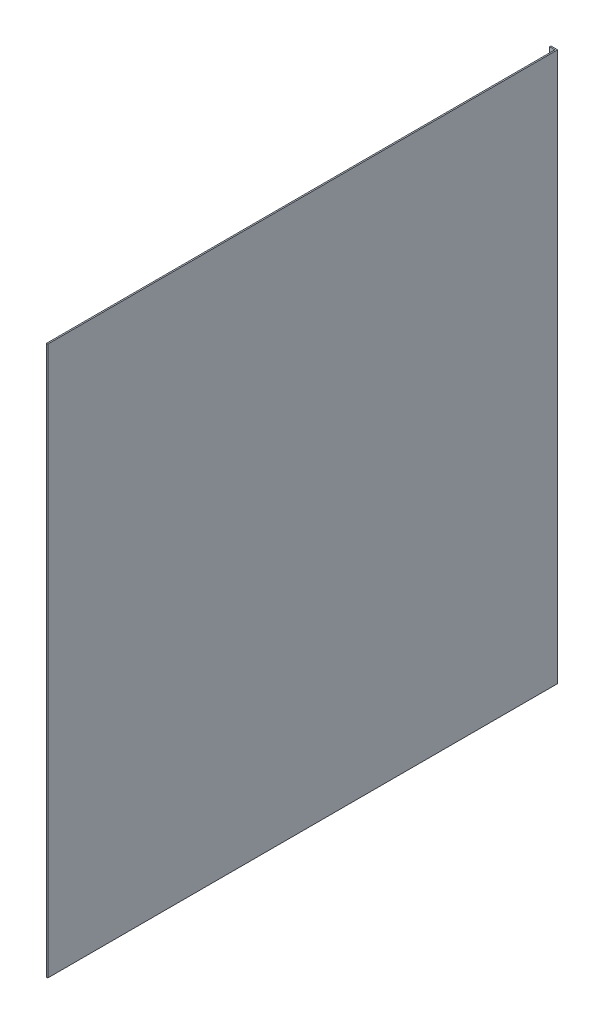
SolidWorks part; units mm, degrees
ref_plane "Front Plane" through (0, 0, 0) normal (0, 0, 1) x (1, 0, 0)
ref_plane "Top Plane" through (0, 0, 0) normal (0, 1, 0) x (1, 0, 0)
ref_plane "Right Plane" through (0, 0, 0) normal (1, 0, 0) x (0, 0, -1)
other "Configuration Table"
sketch "Sketch1" plane through (0, 0, 0) normal (0, 1, 0) x (1, 0, 0)
  line L0 (560, 800) -> (550, 800)
  line L1 (550, 800) -> (550, 798)
  line L2 (550, 798) -> (558, 798)
  line L3 (558, 798) -> (558, 20)
  line L4 (558, 20) -> (560, 20)
  line L5 (560, 20) -> (560, 800)
extrude "PACK_sarjor_L_kilavuz_2_1" add sketch "Sketch1" along normal blind 840 from offset 1040 separate body
